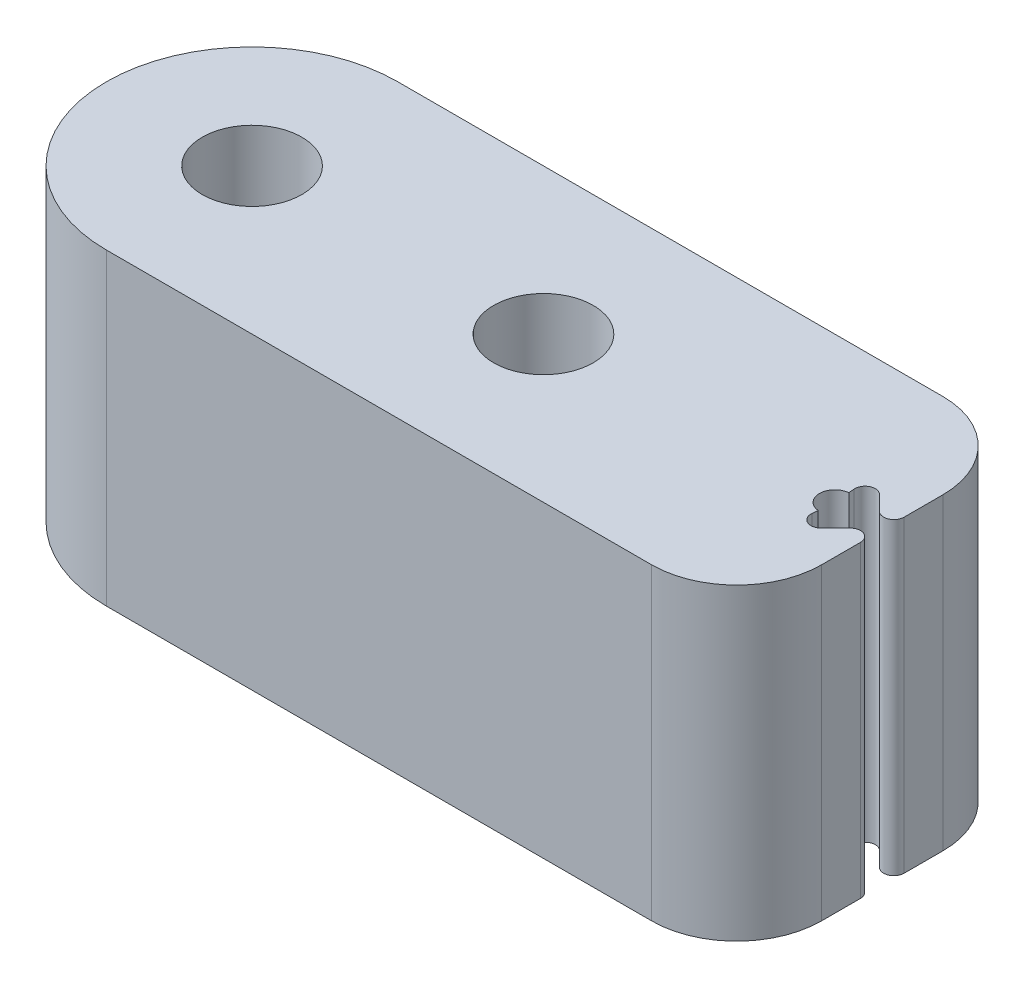
SolidWorks part; units mm, degrees
material "6061 Alloy"
ref_plane "Front Plane" through (0, 0, 0) normal (0, 0, 1) x (1, 0, 0)
ref_plane "Top Plane" through (0, 0, 0) normal (0, 1, 0) x (1, 0, 0)
ref_plane "Right Plane" through (0, 0, 0) normal (1, 0, 0) x (0, 0, -1)
sketch "Sketch1" plane through (0, 0, 0) normal (0, 1, 0) x (1, 0, 0)
  line L0 (0, 0) -> (-4, 0) construction
  line L1 (-4, 0) -> (-4.0553, 0.6326) construction
  line L2 (-4.0553, 0.6326) -> (-4.0758, 0.8669)
  line L3 (-3.3615, 1.2) -> (-2.7615, 0.6)
  line L4 (-4, 0) -> (-3.0808, 0.9192) construction
  line L5 (-6.465, 0.8965) -> (-2.465, 0.8965) construction
  line L6 (-4.0553, -0.6326) -> (-4.0758, -0.8669)
  line L7 (-3.3615, -1.2) -> (-2.7615, -0.6)
  line L8 (-2.0456, 0.8965) -> (-2.0456, 2.5)
  line L12 (-5.5456, 6) -> (-28, 6)
  line L16 (-2.0456, -0.8965) -> (-2.0456, -2.5)
  line L46 (-28, -6) -> (-5.5456, -6)
  circle A0 centre (-4, 0) radius 0.635 construction
  arc A1 (-4.0758, 0.8669) -> (-3.3615, 1.2) centre (-3.6581, 0.9035) cw
  arc A2 (-2.7615, 0.6) -> (-2.0456, 0.8965) centre (-2.465, 0.8965) ccw
  arc A4 (-4.0553, 0.6326) -> (-4.0553, -0.6326) centre (-4, 0) ccw
  arc A5 (-4.0758, -0.8669) -> (-3.3615, -1.2) centre (-3.6581, -0.9035) ccw
  arc A6 (-2.7615, -0.6) -> (-2.0456, -0.8965) centre (-2.465, -0.8965) cw
  arc A63 (-2.0456, 2.5) -> (-5.5456, 6) centre (-5.5456, 2.5) ccw
  circle A65 centre (-16, 0) radius 2.05
  arc A86 (-5.5456, -6) -> (-2.0456, -2.5) centre (-5.5456, -2.5) ccw
  circle A87 centre (-28, 0) radius 2.05
  arc A88 (-28, 6) -> (-28, -6) centre (-28, 0) ccw
  point P0 (0, 0)
  point P34 (-28, -6)
  point P35 (-31.2289, -6)
  point P36 (0, 0)
  point P37 (0, 0)
  point P38 (0, 0)
  dimension "D1" = 1.27
  dimension "D13" = 12
  dimension "D8" = 6
  dimension "D11" = 4.1
  dimension "D9" = 3.5
  dimension "D14" = 12
  dimension "D2" = 4
  dimension "D3" = 95
  dimension "D4" = 45
  dimension "D5" = 1.2
  dimension "D6" = 1.3
  dimension "D7" = 0.6
  dimension "D12" = 12
extrude "Boss-Extrude1" add sketch "Sketch1" along normal blind 12.7
